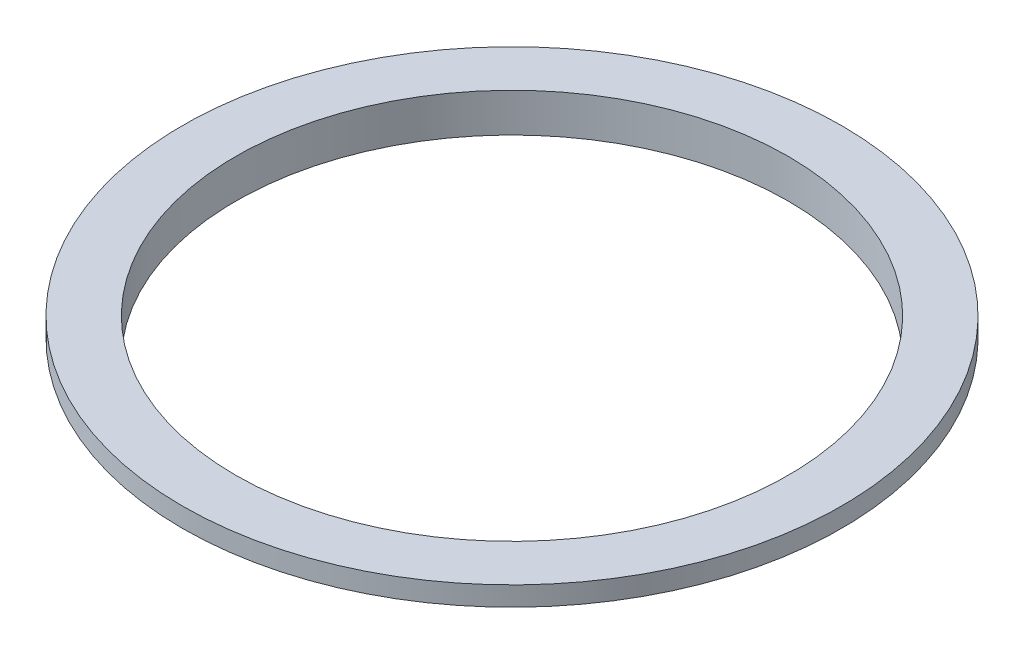
SolidWorks part; units mm, degrees
material "聚脂树脂"
ref_plane "前视基准面" through (0, 0, 0) normal (0, 0, 1) x (1, 0, 0)
ref_plane "上视基准面" through (0, 0, 0) normal (0, 1, 0) x (1, 0, 0)
ref_plane "右视基准面" through (0, 0, 0) normal (1, 0, 0) x (0, 0, -1)
other "Configuration Table"
sketch "草图1" plane through (0, 0, 0) normal (0, 1, 0) x (1, 0, 0)
  circle A0 centre (0, 0) radius 31
  circle A1 centre (0, 0) radius 28.5
  dimension "D1" = 62
  dimension "D2" = 57
extrude "凸台-拉伸1" add sketch "草图1" along normal blind 2
sketch "草图2" plane through (0, 2, 0) normal (0, 1, 0) x (1, 0, 0)
  circle A0 centre (0, 0) radius 28.5
  circle A1 centre (0, 0) radius 34
  dimension "D1" = 57
  dimension "D2" = 68
extrude "凸台-拉伸2" add sketch "草图2" along normal blind 2
